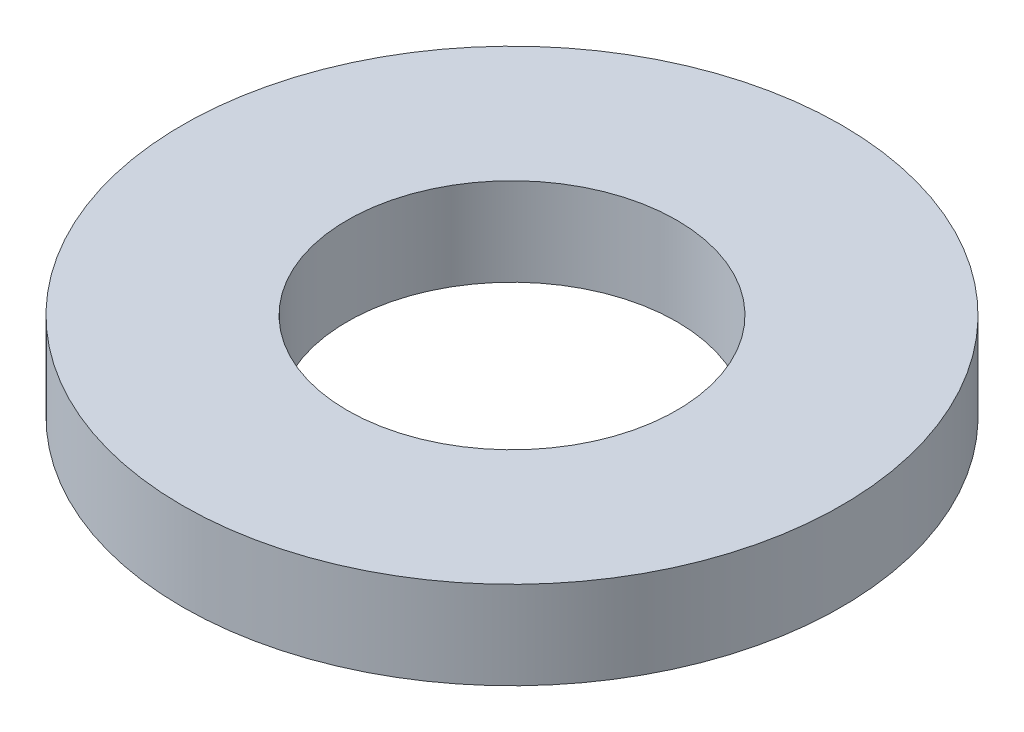
SolidWorks part; units mm, degrees
ref_plane "前视基准面" through (0, 0, 0) normal (0, 0, 1) x (1, 0, 0)
ref_plane "上视基准面" through (0, 0, 0) normal (0, 1, 0) x (1, 0, 0)
ref_plane "右视基准面" through (0, 0, 0) normal (1, 0, 0) x (0, 0, -1)
sketch "草图1" plane through (0, 0, 0) normal (0, 1, 0) x (1, 0, 0)
  circle A0 centre (0, 0) radius 3
  circle A1 centre (0, 0) radius 1.5
  dimension "D1" = 6
  dimension "D2" = 3
extrude "凸台-拉伸1" add sketch "草图1" along normal blind 0.8
